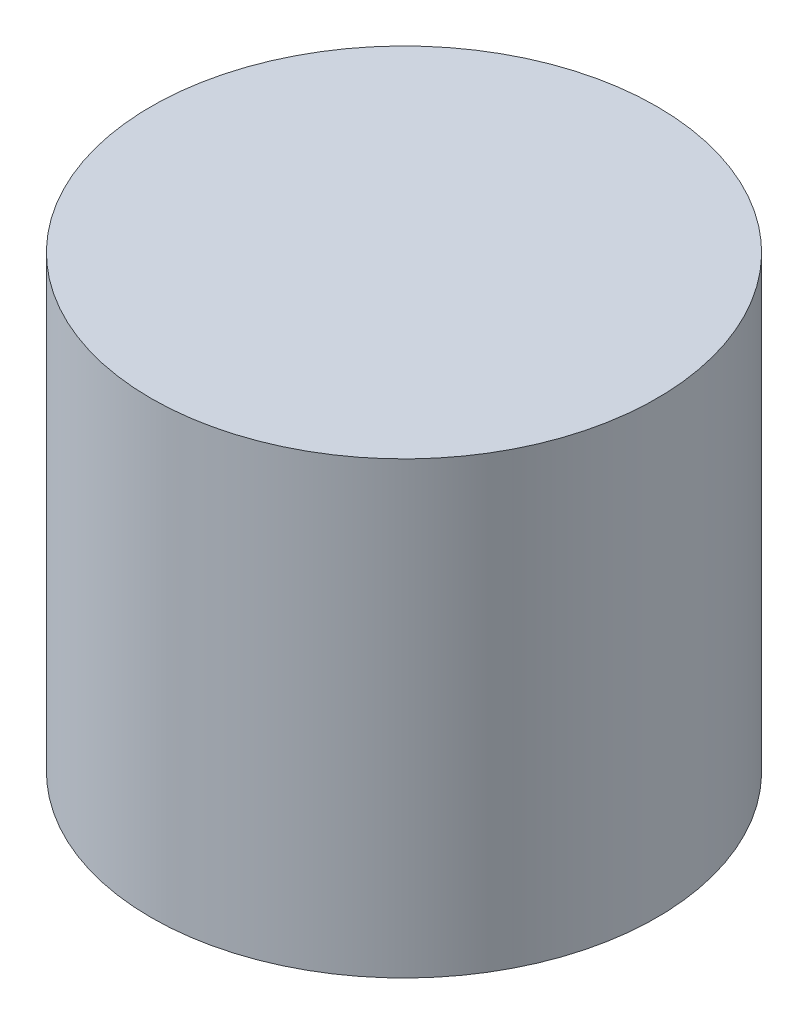
SolidWorks part; units mm, degrees
ref_plane "Front Plane" through (0, 0, 0) normal (0, 0, 1) x (1, 0, 0)
ref_plane "Top Plane" through (0, 0, 0) normal (0, 1, 0) x (1, 0, 0)
ref_plane "Right Plane" through (0, 0, 0) normal (1, 0, 0) x (0, 0, -1)
sketch "Sketch1" plane through (0, 0, 0) normal (0, 1, 0) x (1, 0, 0)
  circle A0 centre (0, 0) radius 22.5
  dimension "D1" = 45
extrude "Boss-Extrude1" add sketch "Sketch1" along normal blind 40
